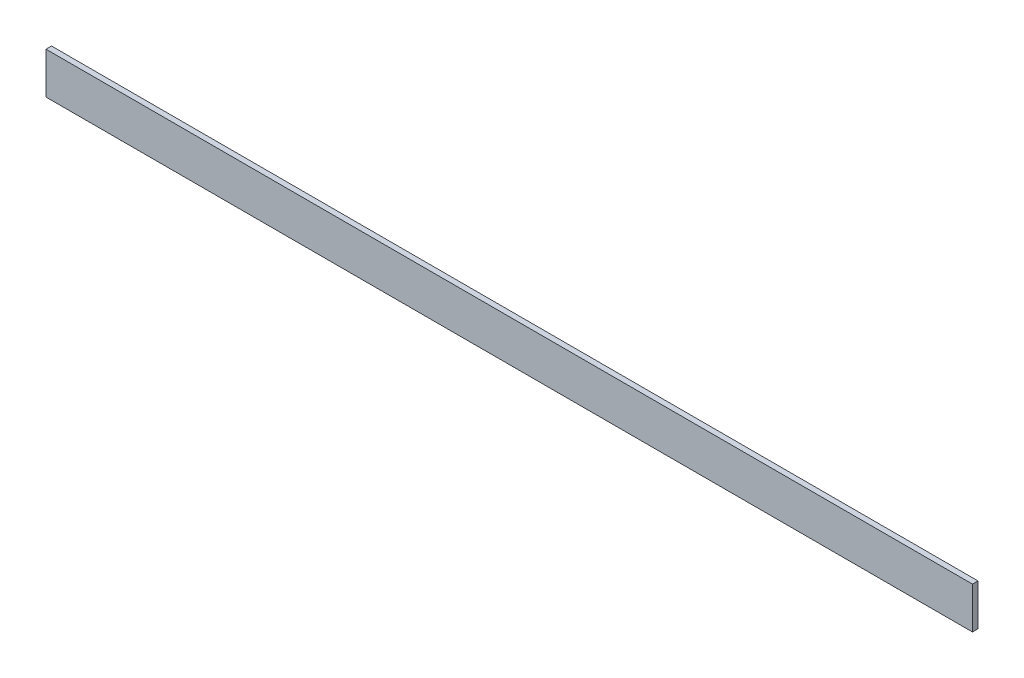
SolidWorks part; units mm, degrees
material "ASTM A36 Steel"
ref_plane "Front Plane" through (0, 0, 0) normal (0, 0, 1) x (1, 0, 0)
ref_plane "Top Plane" through (0, 0, 0) normal (0, 1, 0) x (1, 0, 0)
ref_plane "Right Plane" through (0, 0, 0) normal (1, 0, 0) x (0, 0, -1)
sketch "Sketch1" plane through (0, 0, 0) normal (0, 0, 1) x (1, 0, 0)
  line L1 (-335, -15) -> (335, -15)
  line L2 (-335, -15) -> (-335, 15)
  line L3 (-335, 15) -> (335, 15)
  line L4 (335, -15) -> (335, 15)
  line L5 (-335, -15) -> (335, 15) construction
  line L6 (-335, 15) -> (335, -15) construction
  point P0 (0, 0)
  dimension "D1" = 30
  dimension "D2" = 670
extrude "Boss-Extrude1" add sketch "Sketch1" along normal blind 4
